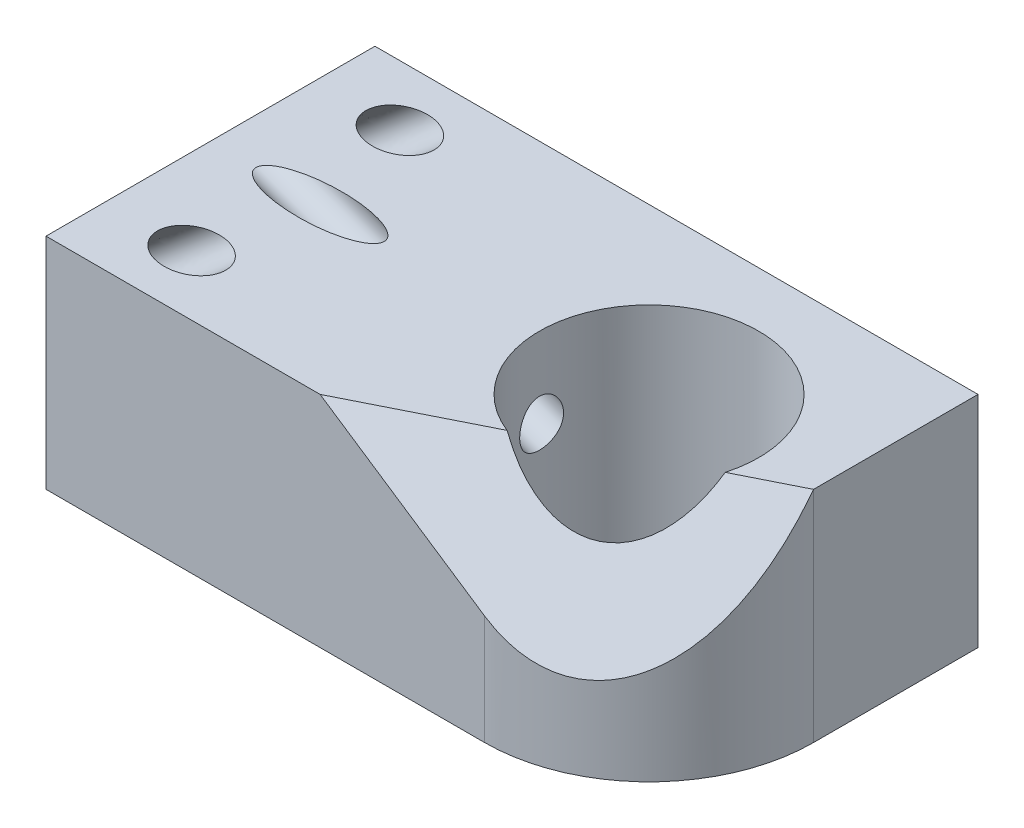
SolidWorks part; units mm, degrees
material "Nickel"
ref_plane "Front Plane" through (0, 0, 0) normal (0, 0, 1) x (1, 0, 0)
ref_plane "Top Plane" through (0, 0, 0) normal (0, 1, 0) x (1, 0, 0)
ref_plane "Right Plane" through (0, 0, 0) normal (1, 0, 0) x (0, 0, -1)
sketch "Sketch1" plane through (0, 0, 0) normal (0, 1, 0) x (1, 0, 0)
  line L1 (-69.85, -38.1) -> (31.75, -38.1)
  line L2 (-69.85, -38.1) -> (-69.85, 38.1)
  line L3 (-69.85, 38.1) -> (69.85, 38.1)
  line L4 (69.85, 0) -> (69.85, 38.1)
  line L5 (-69.85, -38.1) -> (69.85, 38.1) construction
  line L6 (-69.85, 38.1) -> (69.85, -38.1) construction
  circle A0 centre (31.75, 0) radius 25.4
  arc A1 (31.75, -38.1) -> (69.85, 0) centre (31.75, 0) ccw
  point P0 (0, 0)
  dimension "D3" = 50.8
  dimension "D6" = 38.1
  dimension "D1" = 76.2
  dimension "D2" = 139.7
  dimension "D4" = 38.1
  dimension "D5" = 38.1
extrude "Boss-Extrude1" add sketch "Sketch1" along normal blind 50.8
sketch "Sketch2" plane through (0, 0, 38.1) normal (0, 0, 1) x (1, 0, 0)
  line L0 (-6.35, 50.8) -> (31.75, 25.4) construction
  line L1 (-69.85, 50.8) -> (31.75, 50.8) construction
  line L2 (31.75, 50.8) -> (31.75, 0) construction
  dimension "D1" = 38.1
  dimension "D2" = 25.4
ref_plane "Plane1" through (20.1448, 30.2172, 40.2897) normal (0.3714, 0.5571, 0.7428) x (0.9285, -0.2228, -0.2971)
sketch "Sketch3" plane through (20.1448, 30.2172, 40.2897) normal (0.3714, 0.5571, 0.7428) x (0.9285, -0.2228, -0.2971)
  circle A0 centre (6.8392, 17.78) radius 57.7408
  dimension "D1" = 115.4817
extrude "Cut-Extrude1" cut sketch "Sketch3" along normal through all contours A0
ref_plane "Plane2" through (66.0038, 55.3837, 0) normal (0.766, 0.6428, 0) x (0, 0, -1)
sketch "Sketch4" plane through (66.0038, 55.3837, 0) normal (0.766, 0.6428, 0) x (0, 0, -1)
  line L0 (38.1, -5.9837) -> (38.1, 83.8138) construction
  line L1 (-38.1, 83.8138) -> (-38.1, 42.9968) construction
  line L2 (38.1, 83.8138) -> (-38.1, 83.8138) construction
  ellipse E0 centre (-24.13, 71.1138) end of major axis (-17.78, 71.1138) minor radius 5.08
  ellipse E1 centre (24.13, 71.1138) end of major axis (30.48, 71.1138) minor radius 5.08
  point P1 (0, 0)
  point P19 (0, 0)
  point P20 (0, 0)
  dimension "D1" = 6.35
  dimension "D2" = 5.08
  dimension "D3" = 5.08
  dimension "D4" = 6.35
  dimension "D5" = 13.97
  dimension "D6" = 13.97
  dimension "D7" = 12.7
  dimension "D8" = 12.7
extrude "Cut-Extrude2" cut sketch "Sketch4" against normal through all
sketch "Sketch5" plane through (0, 50.8, 0) normal (0, 1, 0) x (1, 0, 0)
  line L0 (-69.85, 38.1) -> (-69.85, -38.1) construction
  line L1 (-69.85, -38.1) -> (-6.35, -38.1) construction
  point P0 (-44.45, 0)
  dimension "D1" = 25.4
  dimension "D2" = 38.1
ref_plane "Plane3" through (-78.0059, 28.3918, 0) normal (-0.9397, 0.342, 0) x (0, 0, 1)
sketch "Sketch6" plane through (-78.0059, 28.3918, 0) normal (-0.9397, 0.342, 0) x (0, 0, 1)
  circle A0 centre (0, 32.5336) radius 5.08
  dimension "D1" = 10.16
extrude "Cut-Extrude3" cut sketch "Sketch6" against normal up to next
